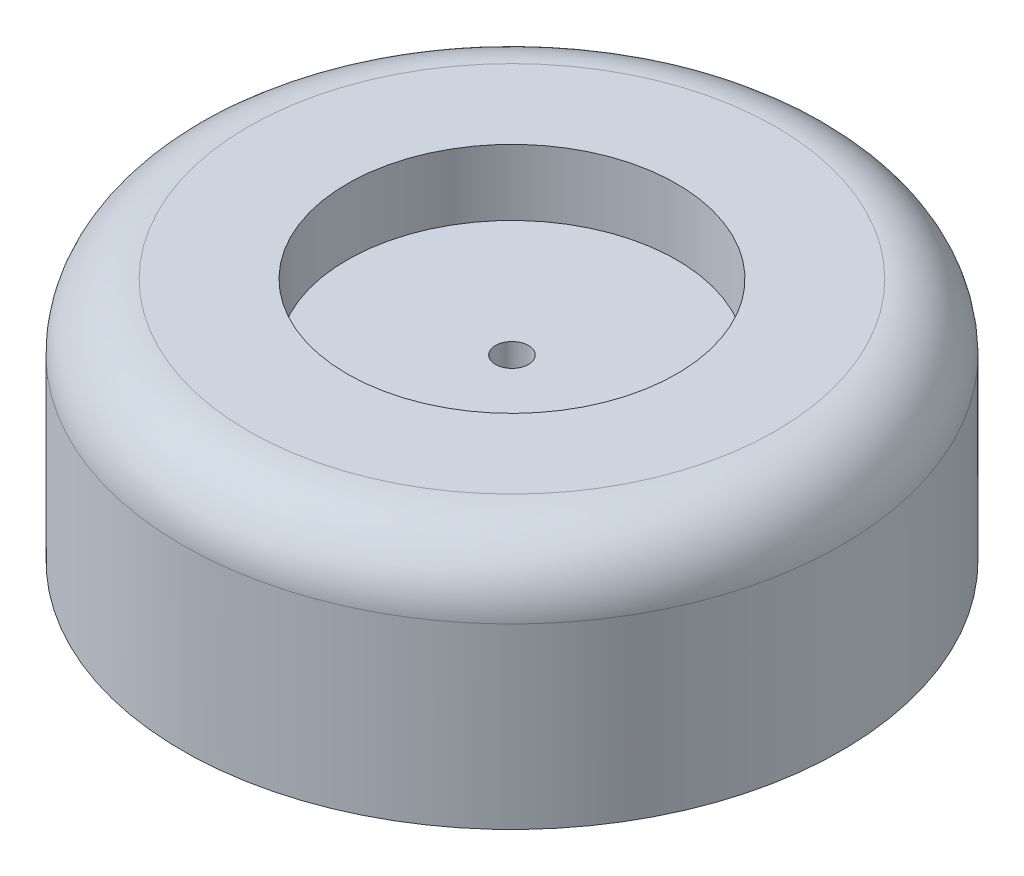
SolidWorks part; units mm, degrees
ref_plane "Front Plane" through (0, 0, 0) normal (0, 0, 1) x (1, 0, 0)
ref_plane "Top Plane" through (0, 0, 0) normal (0, 1, 0) x (1, 0, 0)
ref_plane "Right Plane" through (0, 0, 0) normal (1, 0, 0) x (0, 0, -1)
sketch "Sketch1" plane through (0, 0, 0) normal (0, 1, 0) x (1, 0, 0)
  circle A0 centre (0, 0) radius 47.5
  circle A1 centre (0, 0) radius 50
  dimension "Flange Outer Diameter" = 95
  dimension "Flange Main thickness" = 2.5
extrude "Boss-Extrude1" add sketch "Sketch1" along normal blind 10
sketch "Sketch2" plane through (0, 10, 0) normal (0, 1, 0) x (1, 0, 0)
  circle A0 centre (0, 0) radius 50 construction
  circle A1 centre (0, 0) radius 50
extrude "Boss-Extrude2" add sketch "Sketch2" along normal blind 30
sketch "Sketch3" plane through (0, 10, 0) normal (0, -1, 0) x (1, 0, 0)
  circle A0 centre (0, 0) radius 42.5
  dimension "Bearing track diameter" = 85
sketch "Sketch4" plane through (0, 0, 0) normal (0, 0, 1) x (1, 0, 0)
  line L0 (0, 0) -> (0, 10) construction
  line L1 (-42.5, 10) -> (42.5, 10) construction
  line L2 (0, 10) -> (42.5, 10) construction
  circle A0 centre (42.5, 10) radius 2.5
  dimension "Bearing Ball OD" = 5
  dimension "Bearing track radius" = 42.5
sweep "Cut-Sweep1" cut profiles "Sketch4" path "Sketch3"
sketch "Sketch5" plane through (0, 10, 0) normal (0, -1, 0) x (1, 0, 0)
  circle A0 centre (0, 0) radius 47.5 construction
  circle A1 centre (0, 0) radius 47.5
sketch "Sketch6" plane through (0, 0, 0) normal (0, -1, 0) x (1, 0, 0)
  circle A0 centre (0, 0) radius 50 construction
  circle A1 centre (0, 0) radius 50
extrude "Cut-Extrude2" cut sketch "Sketch6" against normal blind 3
sketch "Sketch7" plane through (0, 40, 0) normal (0, 1, 0) x (1, 0, 0)
  circle A0 centre (0, 0) radius 2.5
  dimension "Center Bolt OD" = 5
extrude "Cut-Extrude3" cut sketch "Sketch7" against normal through all and the other way through all
fillet "Fillet1" radius 10 1 edges at (0, 40, 50)
sketch "Sketch9" plane through (0, 40, 0) normal (0, 1, 0) x (1, 0, 0)
  circle A0 centre (0, 0) radius 25
  dimension "Flange attachment hole" = 50
extrude "Cut-Extrude5" cut sketch "Sketch9" against normal blind 10
